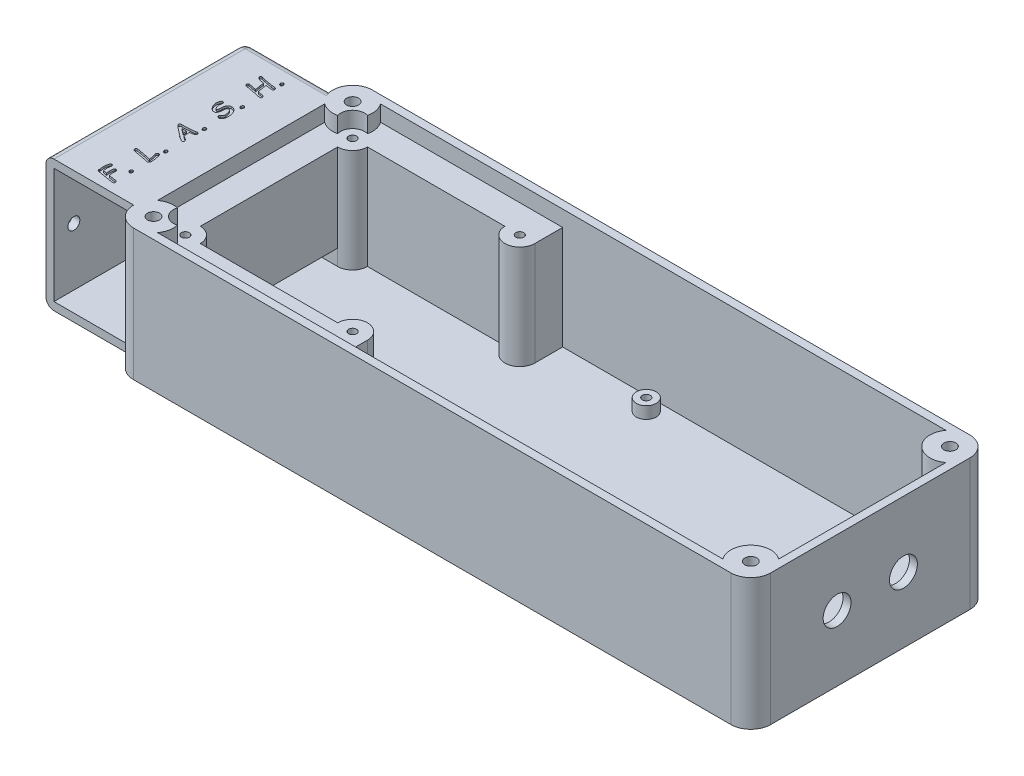
SolidWorks part; units mm, degrees
ref_plane "Front Plane" through (0, 0, 0) normal (0, 0, 1) x (1, 0, 0)
ref_plane "Top Plane" through (0, 0, 0) normal (0, 1, 0) x (1, 0, 0)
ref_plane "Right Plane" through (0, 0, 0) normal (1, 0, 0) x (0, 0, -1)
sketch "Sketch1" plane through (0, 0, 0) normal (0, 1, 0) x (1, 0, 0)
  line L1 (5, 0) -> (155, 0)
  line L2 (0, -5) -> (0, -55)
  line L3 (5, -60) -> (155, -60)
  line L4 (160, -5) -> (160, -55)
  arc A0 (155, 0) -> (160, -5) centre (155, -5) cw
  arc A1 (155, -60) -> (160, -55) centre (155, -55) ccw
  arc A2 (0, -55) -> (5, -60) centre (5, -55) ccw
  arc A3 (5, 0) -> (0, -5) centre (5, -5) ccw
  point P7 (160, 0)
  point P12 (0, -60)
  point P15 (0, 0)
  dimension "D3" = 5
  dimension "D1" = 60
  dimension "D2" = 160
extrude "Boss-Extrude1" add sketch "Sketch1" along normal blind 3
sketch "Sketch2" plane through (0, 3, 0) normal (0, 1, 0) x (1, 0, 0)
  line L0 (7, -2) -> (153, -2)
  line L1 (158, -7) -> (158, -53)
  line L2 (153, -58) -> (7, -58)
  line L3 (2, -53) -> (2, -7)
  line L4 (155, 0) -> (5, 0)
  line L5 (0, -5) -> (0, -55)
  line L6 (5, -60) -> (155, -60)
  line L7 (160, -55) -> (160, -5)
  line L8 (155, 0) -> (5, 0)
  line L9 (0, -5) -> (0, -55)
  line L10 (5, -60) -> (155, -60)
  line L11 (160, -55) -> (160, -5)
  arc A0 (153, -2) -> (158, -7) centre (153, -7) cw
  arc A1 (158, -53) -> (153, -58) centre (153, -53) cw
  arc A2 (7, -58) -> (2, -53) centre (7, -53) cw
  arc A3 (7, -2) -> (2, -7) centre (7, -7) ccw
  arc A4 (160, -5) -> (155, 0) centre (155, -5) ccw
  arc A5 (5, 0) -> (0, -5) centre (5, -5) ccw
  arc A6 (0, -55) -> (5, -60) centre (5, -55) ccw
  arc A7 (155, -60) -> (160, -55) centre (155, -55) ccw
  arc A8 (160, -5) -> (155, 0) centre (155, -5) ccw
  arc A9 (5, 0) -> (0, -5) centre (5, -5) ccw
  arc A10 (0, -55) -> (5, -60) centre (5, -55) ccw
  arc A11 (155, -60) -> (160, -55) centre (155, -55) ccw
  dimension "D6" = 5
  dimension "D2" = 2
  dimension "D3" = 2
  dimension "D4" = 2
  dimension "D5" = 2
  dimension "D1" = 0
extrude "Boss-Extrude2" add sketch "Sketch2" along normal blind 30
sketch "Sketch3" plane through (0, 3, 0) normal (0, 1, 0) x (1, 0, 0)
  line L0 (0, -5) -> (0, -55) construction
  line L1 (9, -9) -> (51, -9) construction
  line L2 (9, -9) -> (9, -51) construction
  line L3 (9, -51) -> (51, -51) construction
  line L4 (51, -9) -> (51, -51) construction
  line L7 (12.75, -9) -> (47.25, -9)
  line L9 (47.25, -51) -> (12.75, -51)
  line L10 (9, -47.25) -> (9, -12.75)
  line L12 (2, -7) -> (2, -53) construction
  line L13 (2, -7) -> (2, -53)
  line L14 (7, -2) -> (54.75, -2)
  line L15 (153, -2) -> (7, -2) construction
  line L17 (7, -58) -> (153, -58) construction
  line L18 (54.75, -58) -> (7, -58)
  line L19 (153, -2) -> (7, -2) construction
  line L20 (54.75, -2) -> (54.75, -9) construction
  line L21 (54.75, -9) -> (54.75, -51) construction
  line L22 (54.75, -51) -> (54.75, -58) construction
  line L28 (54.75, -9) -> (54.75, -2)
  line L29 (54.75, -51) -> (54.75, -58)
  circle A1 centre (9, -9) radius 3.75 construction
  circle A3 centre (51, -9) radius 3.75 construction
  circle A4 centre (51, -51) radius 3.75 construction
  circle A5 centre (9, -51) radius 3.75 construction
  arc A6 (7, -2) -> (2, -7) centre (7, -7) ccw construction
  arc A7 (7, -2) -> (2, -7) centre (7, -7) ccw
  arc A8 (2, -53) -> (7, -58) centre (7, -53) ccw construction
  arc A9 (2, -53) -> (7, -58) centre (7, -53) ccw
  arc A10 (9, -12.75) -> (12.75, -9) centre (9, -9) ccw
  arc A11 (47.25, -9) -> (51, -12.75) centre (51, -9) ccw
  arc A12 (51, -47.25) -> (47.25, -51) centre (51, -51) ccw
  arc A13 (12.75, -51) -> (9, -47.25) centre (9, -51) ccw
  circle A14 centre (9, -9) radius 1
  circle A15 centre (51, -9) radius 1
  circle A16 centre (51, -51) radius 1
  circle A17 centre (9, -51) radius 1
  arc A18 (51, -12.75) -> (54.75, -9) centre (51, -9) ccw
  arc A19 (51, -47.25) -> (54.75, -51) centre (51, -51) cw
  point P4 (0, -30)
  point P7 (9, -30)
  dimension "D3" = 7.5
  dimension "D5" = 2
  dimension "D1" = 42
  dimension "D2" = 42
  dimension "D4" = 7
extrude "Boss-Extrude3" add sketch "Sketch3" along normal blind 26
sketch "Sketch4" plane through (0, 3, 0) normal (0, 1, 0) x (1, 0, 0)
  line L0 (79.25, -3) -> (79.25, -57) construction
  line L1 (79.25, -57) -> (133.75, -57) construction
  line L2 (133.75, -57) -> (133.75, -18) construction
  line L3 (133.75, -18) -> (128.75, -18) construction
  line L4 (128.75, -18) -> (128.75, -3) construction
  line L5 (128.75, -3) -> (79.25, -3) construction
  line L6 (79.25, -3) -> (56.75, -3) construction
  line L7 (56.75, -3) -> (56.75, -57) construction
  line L8 (56.75, -57) -> (79.25, -57) construction
  line L9 (54.75, -9) -> (54.75, -2) construction
  line L10 (9, -47.25) -> (9, -12.75) construction
  circle A0 centre (79.25, -5.5) radius 2.5
  circle A1 centre (79.25, -54.5) radius 2.5
  circle A2 centre (133.75, -49) radius 2.5
  circle A3 centre (133.75, -21) radius 2.5
  circle A4 centre (79.25, -5.5) radius 1
  circle A5 centre (133.75, -21) radius 1
  circle A6 centre (133.75, -49) radius 1
  circle A7 centre (79.25, -54.5) radius 1
  point P12 (9, -30)
  point P13 (56.75, -30)
  dimension "D7" = 5
  dimension "D10" = 2
  dimension "D1" = 5
  dimension "D2" = 77
  dimension "D3" = 54.5
  dimension "D4" = 54
  dimension "D5" = 2
  dimension "D6" = 15
  dimension "D8" = 8
  dimension "D9" = 18
extrude "Boss-Extrude4" add sketch "Sketch4" along normal blind 3
sketch "Sketch5" plane through (0, 0, 0) normal (-1, 0, 0) x (0, 0, 1)
  line L0 (55, 33) -> (55, 31)
  line L1 (55, 33) -> (55, 0) construction
  line L2 (55, 31) -> (7, 31)
  line L3 (7, 31) -> (7, 2)
  line L4 (5, 0) -> (55, 0)
  line L5 (55, 0) -> (55, 33)
  line L6 (55, 33) -> (5, 33)
  line L7 (5, 33) -> (5, 0)
  line L8 (5, 0) -> (55, 0)
  line L10 (55, 33) -> (5, 33)
  line L11 (5, 33) -> (5, 0)
  line L12 (7, 2) -> (55, 2)
  line L13 (55, 2) -> (55, 0)
  dimension "D2" = 2
  dimension "D3" = 2
  dimension "D4" = 2
  dimension "D1" = 0
extrude "Boss-Extrude5" add sketch "Sketch5" along normal blind 20
sketch "Sketch7" plane through (-20, 0, 0) normal (-1, 0, 0) x (0, 0, 1)
  line L1 (5, 33) -> (55, 33)
  line L2 (5, 33) -> (5, 0)
  line L3 (5, 0) -> (55, 0)
  line L4 (55, 33) -> (55, 0)
extrude "Boss-Extrude6" add sketch "Sketch7" along normal blind 2
fillet "Fillet1" radius 2 5 edges at (-22, 33, 30) (-22, 0, 30) (-22, 16.5, 5) (-11, 0, 5) (-11, 33, 5)
sketch "Sketch8" plane through (9, 0, 0) normal (1, 0, 0) x (0, 0, -1)
  line L0 (-12.75, 29) -> (-12.75, 3) construction
  line L1 (-47.25, 3) -> (-12.75, 3)
  line L2 (-47.25, 3) -> (-47.25, 7)
  line L3 (-47.25, 7) -> (-12.75, 7)
  line L4 (-12.75, 3) -> (-12.75, 7)
  dimension "D1" = 4
extrude "Cut-Extrude1" cut sketch "Sketch8" against normal up to surface (9 mm away) up to face at (0, 16.5, 31)
sketch "Sketch9" plane through (160, 0, 0) normal (1, 0, 0) x (0, 0, -1)
  line L0 (-55, 33) -> (-5, 33) construction
  line L3 (-38.3333, 16.5) -> (-21.6667, 16.5) construction
  line L4 (-55, 33) -> (-55, 0) construction
  line L5 (-38.3333, 16.5) -> (-55, 16.5) construction
  line L6 (-21.6667, 16.5) -> (-5, 16.5) construction
  line L7 (-5, 33) -> (-5, 0) construction
  circle A0 centre (-21.6667, 16.5) radius 3.5
  circle A1 centre (-38.3333, 16.5) radius 3.5
  point P2 (-30, 33)
  point P3 (-30, 16.5)
  point P10 (-55, 16.5)
  dimension "D1" = 7
  dimension "D2" = 7
extrude "Cut-Extrude2" cut sketch "Sketch9" against normal up to next
sketch "Sketch10" plane through (0, 3, 0) normal (0, 1, 0) x (1, 0, 0)
  circle A0 centre (155, -5) radius 5
  circle A2 centre (155, -55) radius 5
  circle A3 centre (5, -55) radius 5 construction
  circle A4 centre (5, -5) radius 5 construction
  arc A5 (160, -5) -> (155, 0) centre (155, -5) ccw construction
  arc A6 (155, -60) -> (160, -55) centre (155, -55) ccw construction
  arc A7 (5, 0) -> (0.4174, -7) centre (5, -5) ccw construction
  arc A8 (0, -55) -> (5, -60) centre (5, -55) ccw construction
  circle A9 centre (9, -9) radius 3 construction
  circle A10 centre (9, -51) radius 3 construction
  arc A11 (9.8708, -6.1292) -> (6.1292, -9.8708) centre (5, -5) ccw
  arc A13 (6.1292, -50.1292) -> (9.8708, -53.8708) centre (5, -55) ccw
  arc A14 (9.8708, -53.8708) -> (6.1292, -50.1292) centre (9, -51) cw
  arc A15 (6.1292, -9.8708) -> (9.8708, -6.1292) centre (9, -9) cw
  circle A16 centre (5, -5) radius 1.5
  circle A17 centre (5, -55) radius 1.5
  circle A18 centre (155, -55) radius 1.5
  circle A19 centre (155, -5) radius 1.5
  dimension "D1" = 6
  dimension "D2" = 3
extrude "Boss-Extrude7" add sketch "Sketch10" along normal up to surface (30 mm away) up to face at (59.9561, 33, 30.3797)
sketch "Sketch11" plane through (0, 33, 0) normal (0, 1, 0) x (1, 0, 0)
  line L0 (-7.5, -55) -> (-7.5, -7) construction
  line L1 (-20, -55) -> (0, -55) construction
  line L2 (0.4174, -7) -> (-20, -7) construction
  line L3 (0, -5) -> (0, -55) construction
  text T0 "<b><i>F. L. A. S. H. </i></b>" font "Comic Sans MS" height 4.5
  dimension "D1" = 7.5
extrude "Cut-Extrude3" cut sketch "Sketch11" against normal blind 0.5
sketch "Sketch12" plane through (-22, 0, 0) normal (-1, 0, 0) x (0, 0, 1)
  circle A1 centre (50, 16.5) radius 1.5
  circle A2 centre (50, 16.5) radius 1.5
  dimension "D1" = 0
extrude "Cut-Extrude4" cut sketch "Sketch12" against normal up to next
